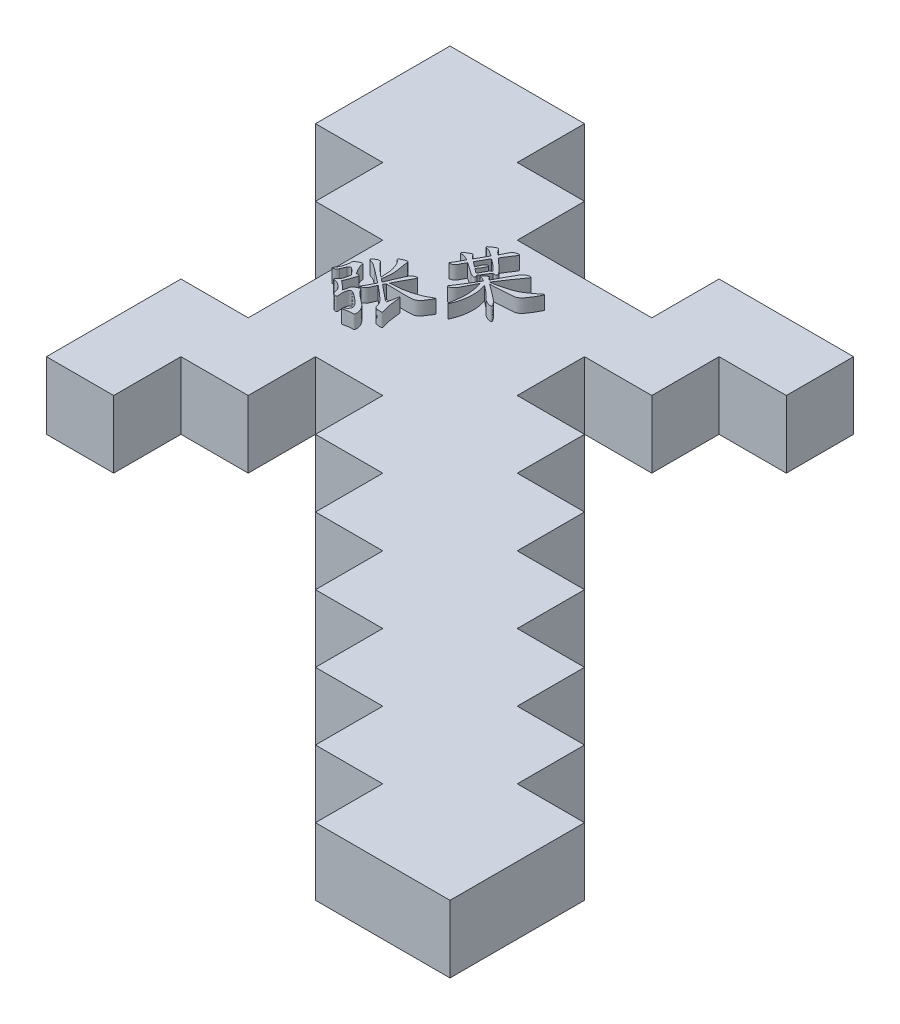
SolidWorks part; units mm, degrees
ref_plane "前视基准面" through (0, 0, 0) normal (0, 0, 1) x (1, 0, 0)
ref_plane "上视基准面" through (0, 0, 0) normal (0, 1, 0) x (1, 0, 0)
ref_plane "右视基准面" through (0, 0, 0) normal (1, 0, 0) x (0, 0, -1)
sketch "草图1" plane through (0, 0, 0) normal (0, 1, 0) x (1, 0, 0)
  line L0 (-63.1302, 0) -> (-58.1302, 0)
  line L29 (-73.1302, -5) -> (-68.1302, -5)
  line L30 (-73.1302, 5) -> (-63.1302, 5)
  line L31 (-68.1302, -10) -> (-68.1302, -5)
  line L32 (-68.1302, -30) -> (-68.1302, -20)
  line L33 (-48.1302, -30) -> (-43.1302, -30)
  line L34 (-63.1302, -30) -> (-63.1302, -25)
  line L35 (-53.1302, -25) -> (-48.1302, -25)
  line L36 (-58.1302, -25) -> (-58.1302, -20)
  line L37 (-43.1302, -10) -> (-43.1302, -5)
  line L38 (-33.1302, -45) -> (-28.1302, -45)
  line L39 (-58.1302, -5) -> (-48.1302, -5)
  line L40 (-63.1302, 0) -> (-63.1302, 5)
  line L41 (-53.1302, -25) -> (-53.1302, -20)
  line L42 (-58.1302, -5) -> (-58.1302, 0)
  line L43 (-48.1302, -5) -> (-48.1302, 0)
  line L44 (-43.1302, -35) -> (-43.1302, -30)
  line L45 (-43.1302, -5) -> (-38.1302, -5)
  line L46 (-48.1302, -10) -> (-43.1302, -10)
  line L47 (-48.1302, -15) -> (-48.1302, -10)
  line L48 (-28.1302, -50) -> (-28.1302, -45)
  line L50 (-18.1302, -50) -> (-18.1302, -40)
  line L51 (-43.1302, -20) -> (-38.1302, -20)
  line L52 (-73.1302, -5) -> (-73.1302, 5)
  line L53 (-38.1302, -5) -> (-38.1302, 0)
  line L54 (-58.1302, -20) -> (-53.1302, -20)
  line L55 (-48.1302, 0) -> (-38.1302, 0)
  line L56 (-63.1302, -20) -> (-63.1302, -10)
  line L57 (-43.1302, -20) -> (-43.1302, -15)
  line L58 (-38.1302, -25) -> (-33.1302, -25)
  line L59 (-38.1302, -25) -> (-38.1302, -20)
  line L60 (-33.1302, -30) -> (-28.1302, -30)
  line L61 (-68.1302, -10) -> (-63.1302, -10)
  line L62 (-33.1302, -30) -> (-33.1302, -25)
  line L63 (-48.1302, -15) -> (-43.1302, -15)
  line L64 (-68.1302, -20) -> (-63.1302, -20)
  line L65 (-63.1302, -25) -> (-58.1302, -25)
  line L66 (-68.1302, -30) -> (-63.1302, -30)
  line L67 (-43.1302, -35) -> (-38.1302, -35)
  line L68 (-38.1302, -40) -> (-33.1302, -40)
  line L69 (-48.1302, -30) -> (-48.1302, -25)
  line L70 (-38.1302, -40) -> (-38.1302, -35)
  line L71 (-33.1302, -45) -> (-33.1302, -40)
  line L72 (-28.1302, -50) -> (-18.1302, -50)
  line L73 (-28.1302, -35) -> (-23.1302, -35)
  line L74 (-28.1302, -35) -> (-28.1302, -30)
  line L75 (-23.1302, -40) -> (-18.1302, -40)
  line L76 (-23.1302, -40) -> (-23.1302, -35)
  dimension "D1" = 5
  dimension "D2" = 5
extrude "凸台-拉伸1" add sketch "草图1" along normal blind 5
sketch "草图7" plane through (0, 5, 0) normal (0, 1, 0) x (1, 0, 0)
  line L0 (-51.5331, -7.2418) -> (-60.406, -18.7771) construction
  text T0 "张某" font "楷体" height 4
extrude "凸台-拉伸3" add sketch "草图7" along normal blind 1
